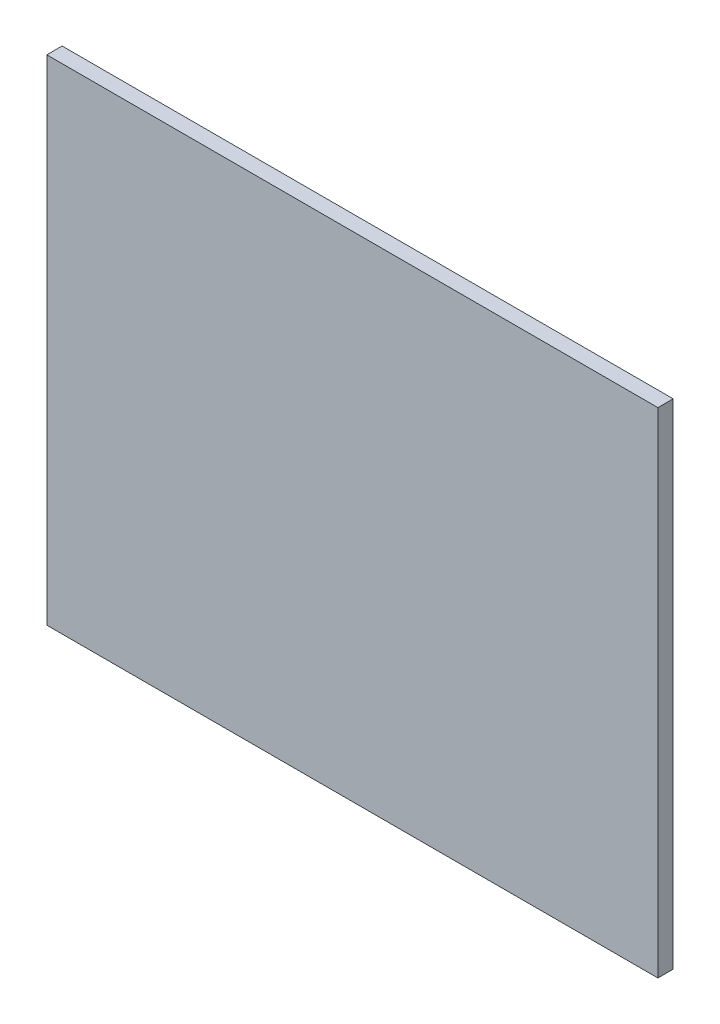
SolidWorks part; units mm, degrees
other "Marcação1"
sketch "Esboço2" plane through (-60, -48.5, 3) normal (0, 0, 1) x (1, 0, 0)
ref_plane "Plano frontal" through (0, 0, 0) normal (0, 0, 1) x (1, 0, 0)
ref_plane "Plano superior" through (0, 0, 0) normal (0, 1, 0) x (1, 0, 0)
ref_plane "Plano direito" through (0, 0, 0) normal (1, 0, 0) x (0, 0, -1)
sketch "Esboço1" plane through (0, 0, 0) normal (0, 0, 1) x (1, 0, 0)
  line L1 (60, -48.5) -> (-60, -48.5)
  line L2 (60, -48.5) -> (60, 48.5)
  line L3 (60, 48.5) -> (-60, 48.5)
  line L4 (-60, -48.5) -> (-60, 48.5)
  line L5 (60, -48.5) -> (-60, 48.5) construction
  line L6 (60, 48.5) -> (-60, -48.5) construction
  point P0 (0, 0)
  dimension "D1" = 120
  dimension "D2" = 97
extrude "Ressalto-extrusão1" add sketch "Esboço1" along normal blind 3
